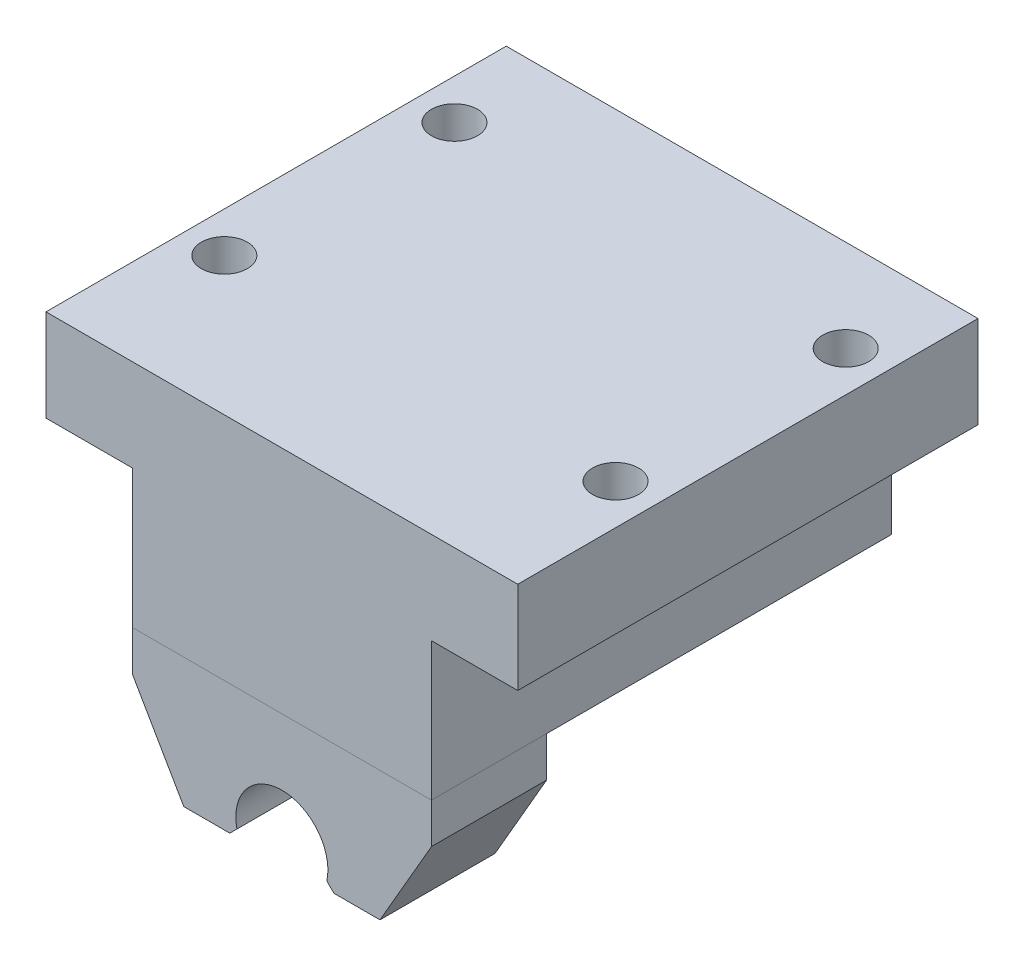
SolidWorks part; units mm, degrees
ref_plane "Front Plane" through (0, 0, 0) normal (0, 0, 1) x (1, 0, 0)
ref_plane "Top Plane" through (0, 0, 0) normal (0, 1, 0) x (1, 0, 0)
ref_plane "Right Plane" through (0, 0, 0) normal (1, 0, 0) x (0, 0, -1)
sketch "Sketch1" plane through (0, 0, 0) normal (0, 0, 1) x (1, 0, 0)
  line L0 (13, -4) -> (20.5, -4)
  line L1 (-20.5, -4) -> (-13, -4)
  line L2 (-20.5, -4) -> (-20.5, 4)
  line L3 (-20.5, 4) -> (20.5, 4)
  line L4 (20.5, -4) -> (20.5, 4)
  line L5 (-20.5, -4) -> (20.5, 4) construction
  line L6 (-20.5, 4) -> (20.5, -4) construction
  line L8 (-13, -4) -> (-13, -16)
  line L9 (-13, -16) -> (13, -16)
  line L10 (13, -4) -> (13, -16)
  point P0 (0, 0)
  dimension "D1" = 41
  dimension "D2" = 8
  dimension "D3" = 7.5
  dimension "D4" = 12
  dimension "D5" = 26
extrude "Boss-Extrude1" add sketch "Sketch1" along normal mid plane 40
sketch "Sketch2" plane through (0, -4, 0) normal (0, -1, 0) x (1, 0, 0)
  line L0 (-20.5, 20) -> (-20.5, -20) construction
  line L1 (-20.5, -20) -> (-13, -20) construction
  line L2 (-17, -12) -> (-17, 8) construction
  line L3 (-17, -12) -> (17, -12) construction
  line L4 (17, -12) -> (17, 8) construction
  line L5 (17, 8) -> (-17, 8) construction
  line L6 (20.5, 20) -> (20.5, -20) construction
  circle A0 centre (-17, -12) radius 2
  circle A1 centre (-17, 8) radius 2
  circle A2 centre (17, -12) radius 2
  circle A3 centre (17, 8) radius 2
  point P12 (15.7515, -12)
  dimension "D1" = 4
  dimension "D2" = 3.5
  dimension "D3" = 8
  dimension "D4" = 28
  dimension "D5" = 3.5
extrude "Cut-Extrude1" cut sketch "Sketch2" against normal blind 10
sketch "Sketch3" plane through (0, -16, 0) normal (0, -1, 0) x (1, 0, 0)
  line L0 (0, 0) -> (0, -4.5) construction
  line L1 (-13, -20) -> (13, -20) construction
  circle A0 centre (0, -4.5) radius 5.075
  dimension "D1" = 10.15
  dimension "D2" = 15.5
extrude "Cut-Extrude2" cut sketch "Sketch3" against normal blind 1.5
sketch "Sketch6" plane through (0, 0, 20) normal (0, 0, 1) x (1, 0, 0)
  line L0 (13, -16) -> (-13, -16)
  line L1 (-13, -16) -> (-13, -19.5)
  line L2 (-13, -19.5) -> (-8.5255, -27.25)
  line L3 (-8.5255, -27.25) -> (-4.5255, -27.25)
  line L4 (-4.5255, -27.25) -> (-3.9026, -26.6271)
  line L5 (13, -16) -> (13, -19.5)
  line L6 (13, -19.5) -> (8.5255, -27.25)
  line L7 (8.5255, -27.25) -> (4.5255, -27.25)
  line L8 (4.5255, -27.25) -> (3.9026, -26.6271)
  arc A0 (3.9026, -26.6271) -> (-3.9026, -26.6271) centre (0, -25.75) ccw
  point P14 (4.1196, -26.5469)
  point P17 (0, 0)
  point P18 (0, -23.9163)
  point P19 (0, -24.6689)
  dimension "D11" = 8
  dimension "D1" = 3.5
  dimension "D2" = 30
  dimension "D3" = 7.75
  dimension "D4" = 4
  dimension "D5" = 3.5
  dimension "D6" = 30
  dimension "D7" = 7.75
  dimension "D8" = 4
  dimension "D9" = 135
  dimension "D10" = 135
  dimension "D12" = 9.75
extrude "Boss-Extrude3" add sketch "Sketch6" against normal blind 10 separate body
